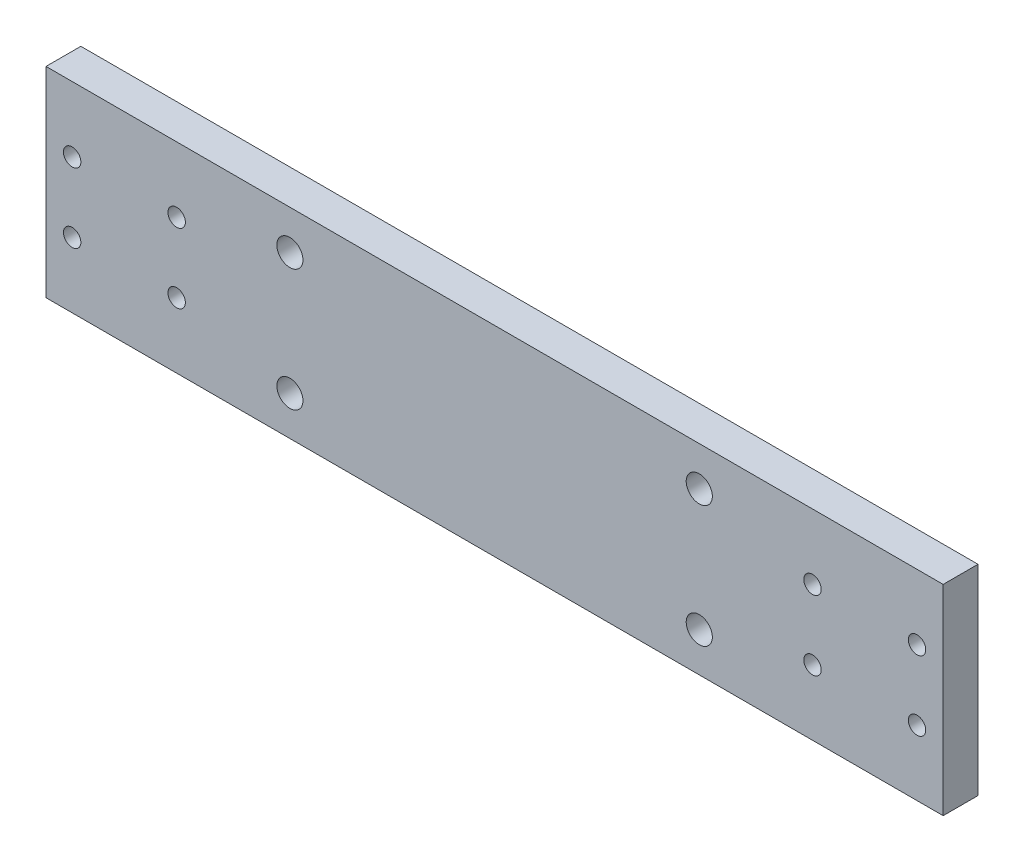
SolidWorks part; units mm, degrees
ref_plane "前视基准面" through (0, 0, 0) normal (0, 0, 1) x (1, 0, 0)
ref_plane "上视基准面" through (0, 0, 0) normal (0, 1, 0) x (1, 0, 0)
ref_plane "右视基准面" through (0, 0, 0) normal (1, 0, 0) x (0, 0, -1)
sketch "草图1" plane through (0, 0, 0) normal (0, 0, 1) x (1, 0, 0)
  line L1 (-51.5, -11.5) -> (51.5, -11.5)
  line L2 (-51.5, -11.5) -> (-51.5, 11.5)
  line L3 (-51.5, 11.5) -> (51.5, 11.5)
  line L4 (51.5, -11.5) -> (51.5, 11.5)
  line L5 (-51.5, -11.5) -> (51.5, 11.5) construction
  line L6 (-51.5, 11.5) -> (51.5, -11.5) construction
  line L7 (-23.5, -7) -> (23.5, -7)
  line L8 (-23.5, -7) -> (-23.5, 7)
  line L9 (-23.5, 7) -> (23.5, 7)
  line L10 (23.5, -7) -> (23.5, 7)
  line L11 (-23.5, -7) -> (23.5, 7) construction
  line L12 (-23.5, 7) -> (23.5, -7) construction
  line L13 (-48.5, 4) -> (-36.5, 4)
  line L14 (-48.5, 4) -> (-48.5, -4)
  line L15 (-48.5, -4) -> (-36.5, -4)
  line L16 (-36.5, 4) -> (-36.5, -4)
  line L17 (36.5, 4) -> (48.5, 4)
  line L18 (36.5, 4) -> (36.5, -4)
  line L19 (36.5, -4) -> (48.5, -4)
  line L20 (48.5, 4) -> (48.5, -4)
  circle A0 centre (-23.5, 7) radius 1.5
  circle A1 centre (-23.5, -7) radius 1.5
  circle A2 centre (23.5, 7) radius 1.5
  circle A3 centre (23.5, -7) radius 1.5
  circle A4 centre (-48.5, 4) radius 1
  circle A5 centre (-36.5, 4) radius 1
  circle A6 centre (-36.5, -4) radius 1
  circle A7 centre (-48.5, -4) radius 1
  circle A8 centre (36.5, 4) radius 1
  circle A9 centre (48.5, 4) radius 1
  circle A10 centre (48.5, -4) radius 1
  circle A11 centre (36.5, -4) radius 1
  point P0 (0, 0)
  point P6 (0, 0)
  point P23 (-48.5, 0)
  point P24 (36.5, 0)
  dimension "D11" = 2
  dimension "D12" = 2
  dimension "D13" = 2
  dimension "D14" = 2
  dimension "D15" = 3
  dimension "D16" = 3
  dimension "D17" = 3
  dimension "D18" = 3
  dimension "D19" = 2
  dimension "D20" = 2
  dimension "D21" = 2
  dimension "D22" = 2
  dimension "D1" = 23
  dimension "D2" = 103
  dimension "D3" = 14
  dimension "D4" = 47
  dimension "D5" = 12
  dimension "D6" = 8
  dimension "D7" = 12
  dimension "D8" = 8
  dimension "D9" = 3
  dimension "D10" = 3
extrude "凸台-拉伸1" add sketch "草图1" along normal blind 4 contours L1 L4 L3 L2 A11 L18 A8 L17 A9 L20 A10 L19 A7 L14 A4 L13 A5 L16 A6 L15 A3 L7 A1 L8 A0 L9 A2 L10 | A7 L15 A6 L16 A5 L13 A4 L14 | A3 L10 A2 L9 A0 L8 A1 L7 | A11 L19 A10 L20 A9 L17 A8 L18
